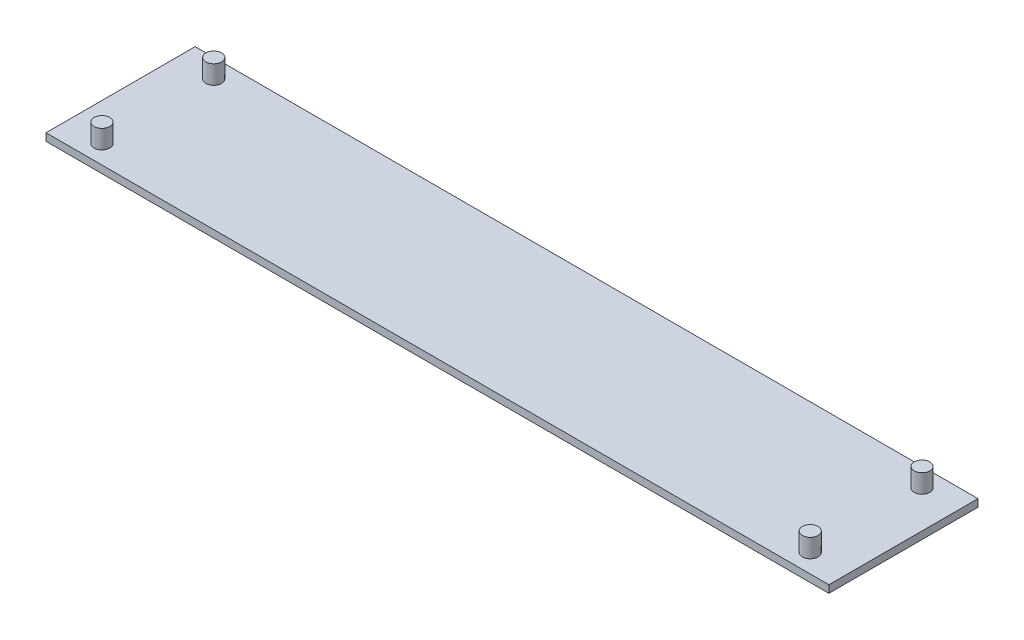
SolidWorks part; units mm, degrees
ref_plane "前视基准面" through (0, 0, 0) normal (0, 0, 1) x (1, 0, 0)
ref_plane "上视基准面" through (0, 0, 0) normal (0, 1, 0) x (1, 0, 0)
ref_plane "右视基准面" through (0, 0, 0) normal (1, 0, 0) x (0, 0, -1)
sketch "草图1" plane through (0, 0, 0) normal (0, 1, 0) x (1, 0, 0)
  line L1 (-105, 20) -> (105, 20)
  line L2 (-105, 20) -> (-105, -20)
  line L3 (-105, -20) -> (105, -20)
  line L4 (105, 20) -> (105, -20)
  line L5 (-105, 20) -> (105, -20) construction
  line L6 (-105, -20) -> (105, 20) construction
  line L7 (-95, 15) -> (95, 15) construction
  line L8 (-95, 15) -> (-95, -15) construction
  line L9 (-95, -15) -> (95, -15) construction
  line L10 (95, 15) -> (95, -15) construction
  line L11 (-95, 15) -> (95, -15) construction
  line L12 (-95, -15) -> (95, 15) construction
  point P0 (0, 0)
  point P6 (0, 0)
  dimension "D1" = 210
  dimension "D2" = 40
  dimension "D3" = 10
  dimension "D4" = 5
extrude "凸台-拉伸1" add sketch "草图1" along normal blind 2
sketch "草图2" plane through (0, 2, 0) normal (0, 1, 0) x (1, 0, 0)
  line L0 (105, -20) -> (105, 20) construction
  line L1 (-95, 15) -> (95, 15) construction
  line L2 (-95, 15) -> (-95, -15) construction
  line L3 (-95, -15) -> (95, -15) construction
  line L4 (95, 15) -> (95, -15) construction
  line L5 (-95, 15) -> (95, -15) construction
  line L6 (-95, -15) -> (95, 15) construction
  line L7 (105, 20) -> (-105, 20) construction
  circle A0 centre (95, -15) radius 2.1
  circle A1 centre (95, 15) radius 2.1
  circle A2 centre (-95, 15) radius 2.1
  circle A3 centre (-95, -15) radius 2.1
  point P0 (0, 0)
  dimension "D3" = 4.2
  dimension "D1" = 10
  dimension "D2" = 5
extrude "凸台-拉伸2" add sketch "草图2" along normal blind 5
